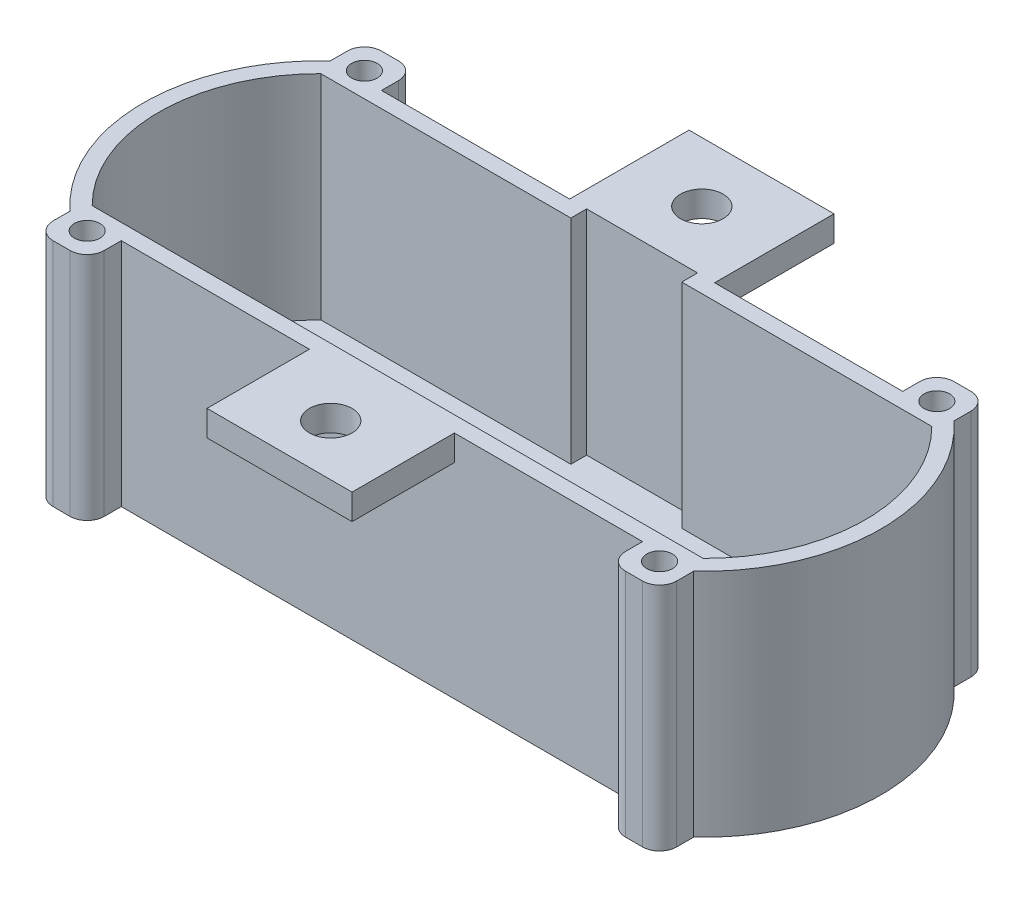
SolidWorks part; units mm, degrees
ref_plane "Front Plane" through (0, 0, 0) normal (0, 0, 1) x (1, 0, 0)
ref_plane "Top Plane" through (0, 0, 0) normal (0, 1, 0) x (1, 0, 0)
ref_plane "Right Plane" through (0, 0, 0) normal (1, 0, 0) x (0, 0, -1)
sketch "Sketch1" plane through (0, 0, 0) normal (0, 1, 0) x (1, 0, 0)
  line L0 (-35.75, 9.7347) -> (-6.5, 9.7347) construction
  line L5 (41.25, -3.5153) -> (31.7962, -3.5153) construction
  line L6 (-35.75, -16.7653) -> (35.75, -16.7653) construction
  line L10 (-35.75, 9.7347) -> (-6.5, 9.7347) construction
  line L11 (-35.75, -16.7653) -> (35.75, -16.7653) construction
  line L12 (-6.5, 11.7347) -> (6.5, 11.7347) construction
  line L13 (8.5, 11.7347) -> (8.5, 25.7347)
  line L14 (-6.5, 11.7347) -> (-6.5, 9.7347) construction
  line L16 (6.5, 11.7347) -> (6.5, 9.7347) construction
  line L18 (6.5, 9.7347) -> (35.75, 9.7347) construction
  line L19 (6.5, 9.7347) -> (35.75, 9.7347) construction
  line L20 (-36.5523, -18.7653) -> (-8.5, -18.7653)
  line L21 (-36.5523, 11.7347) -> (-8.5, 11.7347)
  line L25 (8.5, 11.7347) -> (36.5523, 11.7347)
  line L26 (-8.5, 13.7347) -> (8.5, 13.7347) construction
  line L27 (8.5, 25.7347) -> (-8.5, 25.7347)
  line L28 (8.5, 13.7347) -> (8.5, 11.7347) construction
  line L29 (-8.5, 13.7347) -> (-8.5, 11.7347) construction
  line L30 (-8.5, 25.7347) -> (-8.5, 11.7347)
  line L33 (8.5, -18.7653) -> (36.5523, -18.7653)
  line L34 (-36.5523, -18.7653) -> (36.5523, -18.7653) construction
  line L35 (-8.5, -18.7653) -> (-8.5, -30.7653)
  line L36 (-8.5, -30.7653) -> (8.5, -30.7653)
  line L37 (8.5, -30.7653) -> (8.5, -18.7653)
  arc A0 (35.75, 9.7347) -> (35.75, -16.7653) centre (22.5398, -3.5153) cw construction
  arc A1 (-35.75, 9.7347) -> (-35.75, -16.7653) centre (-22.5398, -3.5153) ccw construction
  arc A2 (36.5523, 11.7347) -> (36.5523, -18.7653) centre (22.5398, -3.5153) cw
  arc A3 (-36.5523, 11.7347) -> (-36.5523, -18.7653) centre (-22.5398, -3.5153) ccw
  point P0 (0, 0)
  point P4 (0, 11.7347)
  dimension "D1" = 13
  dimension "D2" = 2
  dimension "D3" = 71.5
  dimension "D5" = 14
  dimension "D6" = 12
  dimension "D4" = 2
extrude "Boss-Extrude2" add sketch "Sketch1" along normal blind 27
sketch "Sketch4" plane through (0, 27, 0) normal (0, 1, 0) x (1, 0, 0)
  line L0 (6.5, 9.7347) -> (35.75, 9.7347) construction
  line L1 (6.5, 11.7347) -> (6.5, 9.7347) construction
  line L2 (-6.5, 11.7347) -> (6.5, 11.7347) construction
  line L3 (-6.5, 11.7347) -> (-6.5, 9.7347) construction
  line L4 (-35.75, -16.7653) -> (35.75, -16.7653) construction
  line L5 (-35.75, 9.7347) -> (-6.5, 9.7347) construction
  line L6 (6.5, 9.7347) -> (35.75, 9.7347)
  line L7 (6.5, 11.7347) -> (6.5, 9.7347)
  line L8 (-6.5, 11.7347) -> (6.5, 11.7347)
  line L9 (-6.5, 11.7347) -> (-6.5, 9.7347)
  line L10 (-35.75, -16.7653) -> (35.75, -16.7653)
  line L11 (-35.75, 9.7347) -> (-6.5, 9.7347)
  arc A0 (35.75, -16.7653) -> (35.75, 9.7347) centre (22.5398, -3.5153) ccw construction
  arc A1 (-35.75, 9.7347) -> (-35.75, -16.7653) centre (-22.5398, -3.5153) ccw construction
  arc A2 (35.75, -16.7653) -> (35.75, 9.7347) centre (22.5398, -3.5153) ccw
  arc A3 (-35.75, 9.7347) -> (-35.75, -16.7653) centre (-22.5398, -3.5153) ccw
extrude "Cut-Extrude3" cut sketch "Sketch4" against normal blind 25
sketch "Sketch5" plane through (0, 0, 0) normal (0, -1, 0) x (1, 0, 0)
  circle A0 centre (0, 3.5153) radius 10
  dimension "D1" = 20
extrude "Cut-Extrude4" cut sketch "Sketch5" against normal up to surface (2 mm away) up to face at (0, 2, -3.6097)
sketch "Sketch6" plane through (0, 27, 0) normal (0, 1, 0) x (1, 0, 0)
  line L0 (-36.5523, 11.7347) -> (-36.5523, 15.7347)
  line L1 (-36.5523, 15.7347) -> (-30.5523, 15.7347)
  line L2 (-30.5523, 15.7347) -> (-30.5523, 11.7347)
  line L3 (-8.5, 11.7347) -> (-36.5523, 11.7347) construction
  line L4 (-36.5523, 11.7347) -> (-30.5523, 11.7347)
  line L5 (0, -3.5153) -> (5.6116, -3.5153) construction
  line L6 (0, -3.5153) -> (0, -7.7755) construction
  line L7 (-36.5523, -18.7653) -> (-36.5523, -22.7653)
  line L8 (-36.5523, -22.7653) -> (-30.5523, -22.7653)
  line L9 (-30.5523, -22.7653) -> (-30.5523, -18.7653)
  line L10 (-36.5523, -18.7653) -> (-30.5523, -18.7653)
  line L11 (36.5523, -18.7653) -> (30.5523, -18.7653)
  line L12 (30.5523, -22.7653) -> (30.5523, -18.7653)
  line L13 (36.5523, -22.7653) -> (30.5523, -22.7653)
  line L14 (36.5523, -18.7653) -> (36.5523, -22.7653)
  line L15 (36.5523, 11.7347) -> (36.5523, 15.7347)
  line L16 (36.5523, 15.7347) -> (30.5523, 15.7347)
  line L17 (30.5523, 15.7347) -> (30.5523, 11.7347)
  line L18 (36.5523, 11.7347) -> (30.5523, 11.7347)
  dimension "D1" = 4
  dimension "D2" = 6
extrude "Boss-Extrude3" add sketch "Sketch6" against normal up to surface (27 mm away) up to face at (0, 0, -6.4847)
sketch "Sketch7" plane through (0, 27, 0) normal (0, 1, 0) x (1, 0, 0)
  line L0 (-36.5523, 15.7347) -> (-36.5523, 9.7347) construction
  line L1 (-36.5523, 9.7347) -> (-30.5523, 9.7347) construction
  line L2 (-6.5, 9.7347) -> (-35.75, 9.7347) construction
  line L3 (-30.5523, 9.7347) -> (-30.5523, 15.7347) construction
  line L4 (-30.5523, 15.7347) -> (-36.5523, 15.7347) construction
  line L5 (0, -3.5153) -> (5.3611, -3.5153) construction
  line L6 (0, -3.5153) -> (0, -7.7209) construction
  circle A0 centre (-33.5523, 12.7347) radius 1.5
  circle A1 centre (-33.5523, -19.7653) radius 1.5
  circle A2 centre (33.5523, -19.7653) radius 1.5
  circle A3 centre (33.5523, 12.7347) radius 1.5
  dimension "D1" = 3
  dimension "D2" = 3
  dimension "D3" = 3
extrude "Cut-Extrude5" cut sketch "Sketch7" against normal up to surface (27 mm away) up to face at (0, 0, -6.4847)
sketch "Sketch13" plane through (0, 0, 0) normal (0, -1, 0) x (1, 0, 0)
sketch "Sketch15" plane through (0, 0, 0) normal (0, -1, 0) x (1, 0, 0)
  line L0 (-8.5, -13.7347) -> (8.5, -13.7347)
  line L1 (-8.5, -25.7347) -> (-8.5, -11.7347) construction
  line L2 (8.5, -11.7347) -> (8.5, -25.7347) construction
  line L3 (-8.5, -13.7347) -> (-8.5, -25.7347)
  line L4 (-8.5, -25.7347) -> (8.5, -25.7347)
  line L5 (8.5, -25.7347) -> (8.5, -13.7347)
  line L10 (-8.5, 30.7653) -> (-8.5, 18.7653)
  line L11 (-8.5, 18.7653) -> (8.5, 18.7653)
  line L12 (8.5, 18.7653) -> (8.5, 30.7653)
  line L13 (8.5, 30.7653) -> (-8.5, 30.7653)
  dimension "D1" = 2
extrude "Cut-Extrude6" cut sketch "Sketch15" against normal blind 24
fillet "Fillet1" radius 2 8 edges at (-36.5523, 13.5, -15.7347) (-30.5523, 13.5, -15.7347) (36.5523, 13.5, -15.7347) (30.5523, 13.5, -15.7347) (-36.5523, 13.5, 22.7653) (-30.5523, 13.5, 22.7653) (30.5523, 13.5, 22.7653) (36.5523, 13.5, 22.7653)
sketch "Sketch19" plane through (8.5, 0, 0) normal (1, 0, 0) x (0, 0, -1)
  line L0 (25.7347, 24) -> (46.0863, 12.25)
  line L3 (25.7347, 27) -> (25.7347, 24)
  line L5 (25.7347, 27) -> (-30.7653, 27)
  line L6 (-30.7653, 27) -> (-50.1879, -6.641)
  line L11 (25.7347, 27) -> (47.3854, 14.5)
  line L12 (47.3854, 14.5) -> (46.0863, 12.25)
  line L13 (-50.1879, -6.641) -> (-47.5898, -8.141)
  line L14 (-47.5898, -8.141) -> (-29.0332, 24)
  line L15 (-18.7653, 24) -> (-30.7653, 24) construction
  line L16 (-29.0332, 24) -> (-30.7653, 24)
  line L17 (-30.7653, 24) -> (-30.7653, 27)
  dimension "D1" = 3
sketch "Sketch20" plane through (0, 27, 0) normal (0, 1, 0) x (1, 0, 0)
  line L0 (35.75, 9.7347) -> (6.5, 9.7347) construction
  line L1 (-35.75, -16.7653) -> (35.75, -16.7653) construction
  line L2 (-6.5, 9.7347) -> (-35.75, 9.7347) construction
  line L3 (35.75, 9.7347) -> (6.5, 9.7347)
  line L4 (-35.75, -16.7653) -> (35.75, -16.7653)
  line L5 (-6.5, 9.7347) -> (-35.75, 9.7347)
  line L6 (6.5, 9.7347) -> (-6.5, 9.7347)
  line L7 (6.5, 9.8847) -> (-6.5, 9.8847)
  line L8 (-6.5, 9.8847) -> (-35.8119, 9.8847)
  line L9 (-35.8119, -16.9153) -> (35.8119, -16.9153)
  line L10 (35.8119, 9.8847) -> (6.5, 9.8847)
  arc A0 (35.75, -16.7653) -> (35.75, 9.7347) centre (22.5398, -3.5153) ccw construction
  arc A1 (-35.75, 9.7347) -> (-35.75, -16.7653) centre (-22.5398, -3.5153) ccw construction
  arc A2 (35.75, -16.7653) -> (35.75, 9.7347) centre (22.5398, -3.5153) ccw
  arc A3 (-35.75, 9.7347) -> (-35.75, -16.7653) centre (-22.5398, -3.5153) ccw
  arc A4 (-35.8119, 9.8847) -> (-35.8119, -16.9153) centre (-22.5398, -3.5153) ccw
  arc A5 (35.8119, -16.9153) -> (35.8119, 9.8847) centre (22.5398, -3.5153) ccw
  dimension "D1" = 0.15
extrude "Cut-Extrude10" cut sketch "Sketch20" against normal up to surface (25 mm away) up to face at (0, 2, 13.5153)
sketch "Sketch21" plane through (0, 27, 0) normal (0, 1, 0) x (1, 0, 0)
  circle A0 centre (0, 18.7347) radius 2.5
  circle A1 centre (0, -24.7653) radius 2.5
extrude "Cut-Extrude11" cut sketch "Sketch21" against normal blind 10
